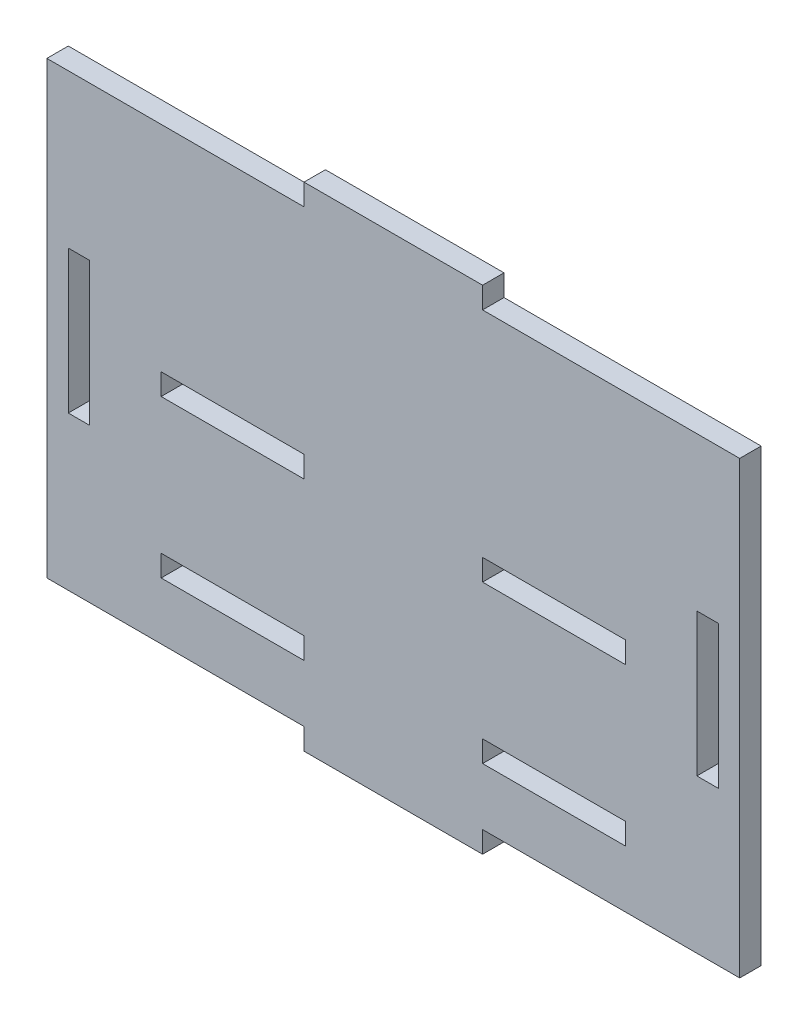
SolidWorks part; units mm, degrees
ref_plane "Front Plane" through (0, 0, 0) normal (0, 0, 1) x (1, 0, 0)
ref_plane "Top Plane" through (0, 0, 0) normal (0, 1, 0) x (1, 0, 0)
ref_plane "Right Plane" through (0, 0, 0) normal (1, 0, 0) x (0, 0, -1)
sketch "Sketch1" plane through (0, 0, 0) normal (0, 0, 1) x (1, 0, 0)
  line L1 (-42.5, 31.5) -> (42.5, 31.5)
  line L2 (-42.5, 31.5) -> (-42.5, -31.5)
  line L3 (-42.5, -31.5) -> (42.5, -31.5)
  line L4 (42.5, 31.5) -> (42.5, -31.5)
  line L5 (-42.5, 31.5) -> (42.5, -31.5) construction
  line L6 (-42.5, -31.5) -> (42.5, 31.5) construction
  point P0 (0, 0)
  dimension "D1" = 85
  dimension "D2" = 63
extrude "Boss-Extrude1" add sketch "Sketch1" along normal blind 3
sketch "Sketch2" plane through (0, 0, 3) normal (0, 0, 1) x (1, 0, 0)
  line L0 (0, 31.5) -> (0, -31.5) construction
  line L1 (-32.5, 1.5) -> (-12.5, 1.5)
  line L2 (-32.5, 1.5) -> (-32.5, -1.5)
  line L3 (-32.5, -1.5) -> (-12.5, -1.5)
  line L4 (-12.5, 1.5) -> (-12.5, -1.5)
  line L5 (-32.5, 1.5) -> (-12.5, -1.5) construction
  line L6 (-32.5, -1.5) -> (-12.5, 1.5) construction
  line L7 (32.5, 1.5) -> (12.5, 1.5)
  line L8 (32.5, 1.5) -> (32.5, -1.5)
  line L9 (32.5, -1.5) -> (12.5, -1.5)
  line L10 (12.5, 1.5) -> (12.5, -1.5)
  line L11 (32.5, 1.5) -> (12.5, -1.5) construction
  line L12 (32.5, -1.5) -> (12.5, 1.5) construction
  line L13 (42.5, 31.5) -> (-42.5, 31.5) construction
  line L14 (-42.5, -31.5) -> (42.5, -31.5) construction
  line L15 (-42.5, 0) -> (-22.5, 0) construction
  line L16 (-42.5, -22) -> (-22.5, -22) construction
  line L17 (-12.5, -20.5) -> (-32.5, -20.5)
  line L18 (-42.5, 31.5) -> (-42.5, -31.5) construction
  line L19 (-22.5, 0) -> (22.5, 0) construction
  line L20 (22.5, 0) -> (42.5, 0) construction
  line L21 (42.5, -31.5) -> (42.5, 31.5) construction
  line L22 (-12.5, -20.5) -> (-12.5, -23.5)
  line L23 (-12.5, -23.5) -> (-32.5, -23.5)
  line L24 (-32.5, -20.5) -> (-32.5, -23.5)
  line L25 (-12.5, -20.5) -> (-32.5, -23.5) construction
  line L26 (-12.5, -23.5) -> (-32.5, -20.5) construction
  line L27 (32.5, -20.5) -> (12.5, -20.5)
  line L28 (32.5, -20.5) -> (32.5, -23.5)
  line L29 (32.5, -23.5) -> (12.5, -23.5)
  line L30 (12.5, -20.5) -> (12.5, -23.5)
  line L31 (32.5, -20.5) -> (12.5, -23.5) construction
  line L32 (32.5, -23.5) -> (12.5, -20.5) construction
  line L33 (-22.5, -22) -> (22.5, -22) construction
  line L34 (22.5, -22) -> (42.5, -22) construction
  point P0 (-22.5, 0)
  point P5 (22.5, 0)
  point P20 (-22.5, -22)
  point P29 (22.5, -22)
  dimension "D1" = 3
  dimension "D2" = 20
  dimension "D3" = 20
  dimension "D4" = 30
  dimension "D5" = 8
extrude "Cut-Extrude1" cut sketch "Sketch2" against normal through all
sketch "Sketch3" plane through (0, 0, 3) normal (0, 0, 1) x (1, 0, 0)
  line L0 (-42.5, 31.5) -> (-48.5, 31.5)
  line L1 (-48.5, 31.5) -> (-48.5, -31.5)
  line L2 (-48.5, -31.5) -> (-42.5, -31.5)
  line L3 (-42.5, -31.5) -> (-42.5, -10)
  line L4 (-42.5, 31.5) -> (-42.5, -31.5) construction
  line L5 (-42.5, -10) -> (-45.5, -10)
  line L6 (-45.5, -10) -> (-45.5, 10)
  line L7 (-45.5, 10) -> (-42.5, 10)
  line L8 (-42.5, 10) -> (-42.5, 31.5)
  line L9 (-45.5, 0) -> (0, 0) construction
  line L10 (0, 31.5) -> (0, -31.5) construction
  line L11 (42.5, 31.5) -> (-42.5, 31.5) construction
  line L12 (-42.5, -31.5) -> (42.5, -31.5) construction
  line L13 (42.5, 10) -> (42.5, 31.5)
  line L14 (45.5, 10) -> (42.5, 10)
  line L15 (45.5, -10) -> (45.5, 10)
  line L16 (42.5, -10) -> (45.5, -10)
  line L17 (42.5, -31.5) -> (42.5, -10)
  line L18 (48.5, -31.5) -> (42.5, -31.5)
  line L19 (48.5, 31.5) -> (48.5, -31.5)
  line L20 (42.5, 31.5) -> (48.5, 31.5)
  dimension "D1" = 6
  dimension "D2" = 3
  dimension "D3" = 20
extrude "Boss-Extrude2" add sketch "Sketch3" against normal up to surface (3 mm away) up to face at (22.5, -22, 0)
sketch "Sketch4" plane through (0, 0, 3) normal (0, 0, 1) x (1, 0, 0)
  line L0 (0, -31.5) -> (0, 0) construction
  line L1 (-12.5, 34.5) -> (12.5, 34.5)
  line L2 (-12.5, 34.5) -> (-12.5, 31.5)
  line L3 (-12.5, 31.5) -> (12.5, 31.5)
  line L4 (12.5, 34.5) -> (12.5, 31.5)
  line L5 (-12.5, 34.5) -> (12.5, 31.5) construction
  line L6 (-12.5, 31.5) -> (12.5, 34.5) construction
  line L7 (-12.5, -34.5) -> (12.5, -34.5)
  line L8 (-12.5, -34.5) -> (-12.5, -31.5)
  line L9 (-12.5, -31.5) -> (12.5, -31.5)
  line L10 (12.5, -34.5) -> (12.5, -31.5)
  line L11 (-12.5, -34.5) -> (12.5, -31.5) construction
  line L12 (-12.5, -31.5) -> (12.5, -34.5) construction
  line L13 (0, 0) -> (0, 31.5) construction
  line L14 (-48.5, -31.5) -> (48.5, -31.5) construction
  line L15 (48.5, 31.5) -> (-48.5, 31.5) construction
  point P0 (0, 33)
  point P5 (0, -33)
  dimension "D1" = 3
  dimension "D2" = 25
extrude "Boss-Extrude3" add sketch "Sketch4" against normal up to surface (3 mm away) up to face at (0, 0, 0)
